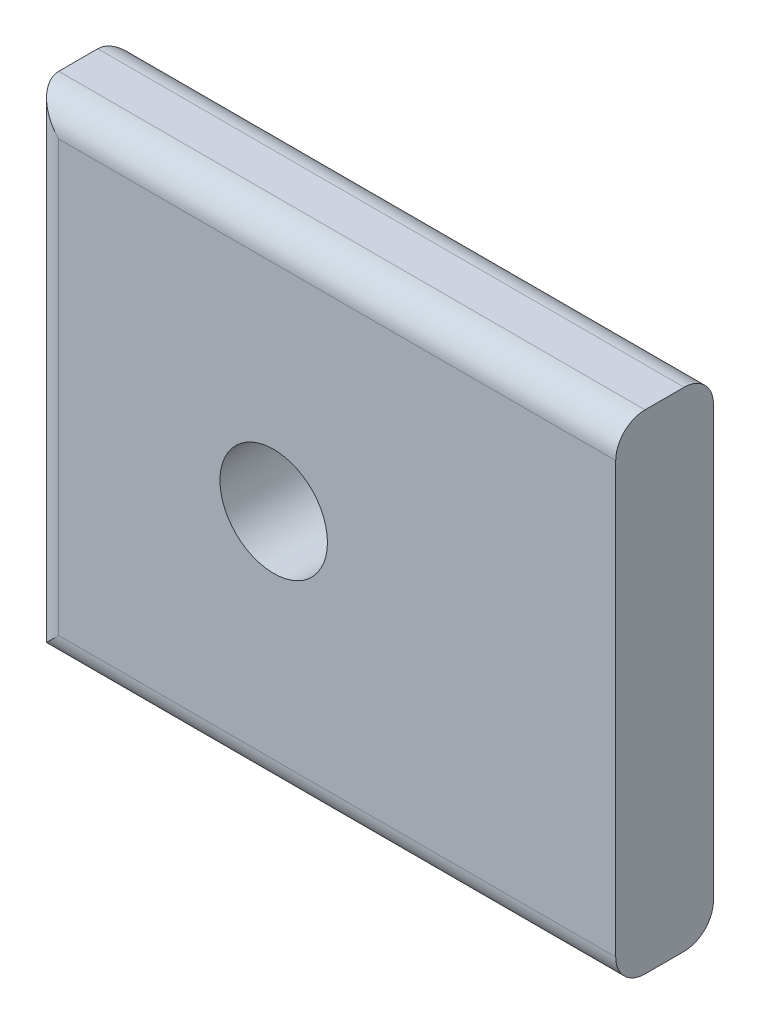
SolidWorks part; units mm, degrees
material "普通碳钢"
ref_plane "前视基准面" through (0, 0, 0) normal (0, 0, 1) x (1, 0, 0)
ref_plane "上视基准面" through (0, 0, 0) normal (0, 1, 0) x (1, 0, 0)
ref_plane "右视基准面" through (0, 0, 0) normal (1, 0, 0) x (0, 0, -1)
sketch "草图1" plane through (0, 0, 0) normal (0, 0, 1) x (1, 0, 0)
  line L1 (-30, 25) -> (30, 25)
  line L2 (-30, 25) -> (-30, -25)
  line L3 (-30, -25) -> (30, -25)
  line L4 (30, 25) -> (30, -25)
  line L5 (-30, 25) -> (30, -25) construction
  line L6 (-30, -25) -> (30, 25) construction
  point P0 (0, 0)
  dimension "D1" = 50
  dimension "D2" = 60
extrude "凸台-拉伸1" add sketch "草图1" along normal blind 10
sketch "草图2" plane through (0, 0, 10) normal (0, 0, 1) x (1, 0, 0)
  line L1 (-30, 25) -> (-30, -25) construction
  line L3 (30, 25) -> (-30, 25) construction
  circle A0 centre (-5, 0) radius 5.5
  dimension "D1" = 11
  dimension "D2" = 25
  dimension "D3" = 25
extrude "切除-拉伸1" cut sketch "草图2" against normal blind 10
ref_plane "基准面1" through (0, 0, 5) normal (0, 0, 1) x (1, 0, 0)
fillet "圆角1" radius 3 6 edges at (0, 25, 10) (0, -25, 0) (0, -25, 10) (-30, 0, 10) (-30, 0, 0) (0, 25, 0)
